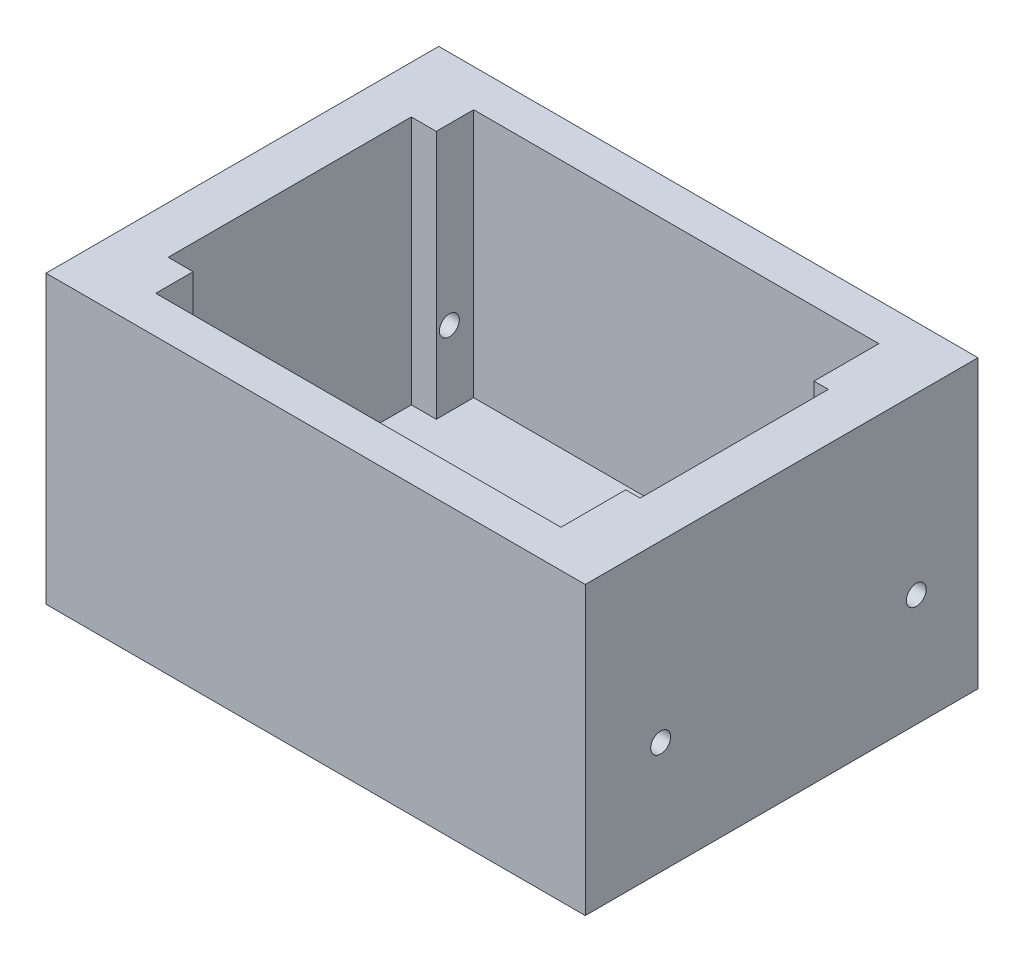
SolidWorks part; units mm, degrees
ref_plane "Front Plane" through (0, 0, 0) normal (0, 0, 1) x (1, 0, 0)
ref_plane "Top Plane" through (0, 0, 0) normal (0, 1, 0) x (1, 0, 0)
ref_plane "Right Plane" through (0, 0, 0) normal (1, 0, 0) x (0, 0, -1)
sketch "Sketch1" plane through (0, 0, 0) normal (0, 1, 0) x (1, 0, 0)
  line L1 (0, 0) -> (43.25, 0)
  line L2 (0, 0) -> (0, 31.5)
  line L3 (0, 31.5) -> (43.25, 31.5)
  line L4 (43.25, 0) -> (43.25, 31.5)
  dimension "D1" = 31.5
  dimension "D2" = 43.25
extrude "Boss-Extrude1" add sketch "Sketch1" along normal blind 23
sketch "Sketch2" plane through (0, 23, 0) normal (0, 1, 0) x (1, 0, 0)
  line L0 (21.5, 34.3711) -> (21.5, -3.2198) construction
  line L1 (0, 31.5) -> (0, 0) construction
  line L2 (38.3, 28.5) -> (5.8, 28.5)
  line L3 (5.8, 28.5) -> (5.8, 25.5)
  line L4 (5.8, 25.5) -> (3.8, 25.5)
  line L5 (3.8, 25.5) -> (3.8, 6)
  line L6 (3.8, 6) -> (5.8, 6)
  line L7 (5.8, 6) -> (5.8, 3)
  line L8 (5.8, 3) -> (38.3, 3)
  line L9 (38.3, 3) -> (38.3, 8.2)
  line L10 (38.3, 8.2) -> (39.45, 8.2)
  line L11 (39.45, 8.2) -> (39.45, 23.3)
  line L12 (39.45, 23.3) -> (38.3, 23.3)
  line L13 (38.3, 23.3) -> (38.3, 28.5)
  line L15 (0, 0) -> (43.25, 0) construction
  line L16 (43.25, 0) -> (43.25, 31.5) construction
  dimension "D1" = 21.5
  dimension "D2" = 1.15
  dimension "D3" = 32.5
  dimension "D4" = 3
  dimension "D5" = 19.5
  dimension "D6" = 5.2
  dimension "D7" = 15.1
  dimension "D8" = 3.8
  dimension "D9" = 2
  dimension "D10" = 2
  dimension "D11" = 3
  dimension "D12" = 3
  dimension "D13" = 3.8
extrude "Cut-Extrude1" cut sketch "Sketch2" against normal blind 20
sketch "Sketch3" plane through (38.3, 0, 0) normal (-1, 0, 0) x (0, 0, 1)
  line L3 (-8.2, 3) -> (-8.2, 23) construction
  line L4 (-8.2, 3) -> (-23.3, 3) construction
  line L5 (-23.3, 3) -> (-23.3, 23) construction
  line L6 (-8.2, 3) -> (-8.2, 23)
  line L7 (-8.2, 3) -> (-23.3, 3)
  line L8 (-23.3, 3) -> (-23.3, 23)
  circle A2 centre (-26.55, 9) radius 0.8
  circle A3 centre (-6.05, 9) radius 0.8
  dimension "D5" = 1.6
  dimension "D6" = 6
  dimension "D7" = 20.5
  dimension "D8" = 3.25
extrude "Cut-Extrude2" cut sketch "Sketch3" against normal through all both and the other way through all contours A2 | A3
sketch "Sketch4" plane through (5.8, 0, 0) normal (1, 0, 0) x (0, 0, -1)
  line L3 (25.5, 3) -> (25.5, 23) construction
  line L4 (25.5, 3) -> (6, 3) construction
  line L5 (6, 3) -> (6, 8.2016) construction
  line L6 (25.5, 3) -> (25.5, 23)
  line L7 (25.5, 3) -> (6, 3)
  line L8 (6, 3) -> (6, 8.2016)
  circle A2 centre (5, 5.4) radius 0.8
  circle A3 centre (25.5, 5.4) radius 0.8
  dimension "D5" = 1.6
  dimension "D6" = 20.5
  dimension "D7" = 1
  dimension "D8" = 2.4
extrude "Cut-Extrude3" [suppressed] cut sketch "Sketch4" against normal up to surface (2.8 mm away) contours A3 | A2
